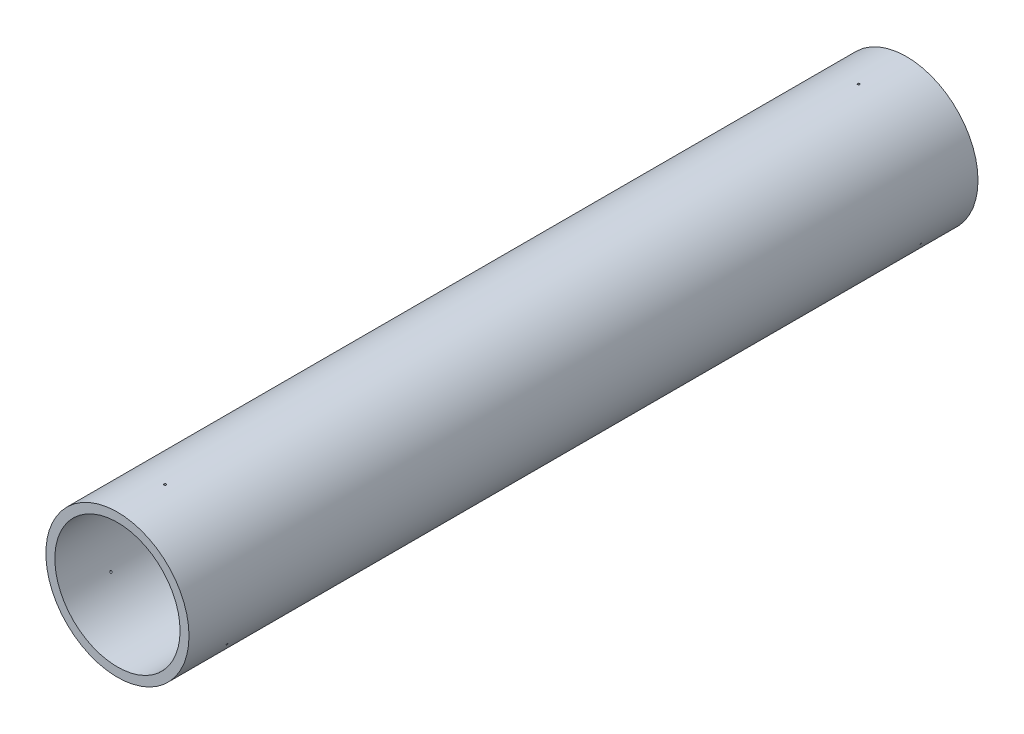
SolidWorks part; units mm, degrees
ref_plane "Front" through (0, 0, 0) normal (0, 0, 1) x (1, 0, 0)
ref_plane "Top" through (0, 0, 0) normal (0, 1, 0) x (1, 0, 0)
ref_plane "Right" through (0, 0, 0) normal (1, 0, 0) x (0, 0, -1)
sketch "Sketch1" plane through (0, 0, 0) normal (0, 0, 1) x (1, 0, 0)
  circle A0 centre (0, 0) radius 66.6496
  circle A1 centre (0, 0) radius 76.1746
  dimension "D1" = 152.3492
  dimension "D2" = 9.525
extrude "Boss-Extrude1" add sketch "Sketch1" along normal mid plane 839.7748
hole_wizard "#4-40 Tapped Hole1" positions "3DSketch2" profile "Sketch3" tap size "#4-40" standard "ANSI Inch"
sketch3d "3DSketch2"
  point P0 (0, 76.1746, 369.0874)
  dimension "D1" = 50.8
sketch "Sketch3" plane through (0, 76.1746, 369.0874) normal (1, 0, 0) x (0, 0, 1)
  line L0 (0, 0) -> (0, 152.3492)
  line L1 (0, 152.3492) -> (1.1303, 152.3492)
  line L2 (1.1303, 152.3492) -> (1.1303, 0)
  line L5 (1.1303, 0) -> (0, 0)
  line L11 (0, -6.35) -> (0, 107.95) construction
  dimension "Thru Tap Drill Dia." = 2.2606
  dimension "Thru Tap Drill Depth" = 152.3492
cosmetic thread "Hole Thread2" parameters "D2"=2.8448
pattern_circular "CirPattern1" count 3 over 360 about axis through (0, 0, 419.8874) along (0, 0, 1) of "#4-40 Tapped Hole1"
mirror "Mirror1" about plane through (0, 0, 0) normal (0, 0, 1) of "CirPattern1", "#4-40 Tapped Hole1"
chamfer "Chamfer1" [suppressed] distance 0.254 angle 45
